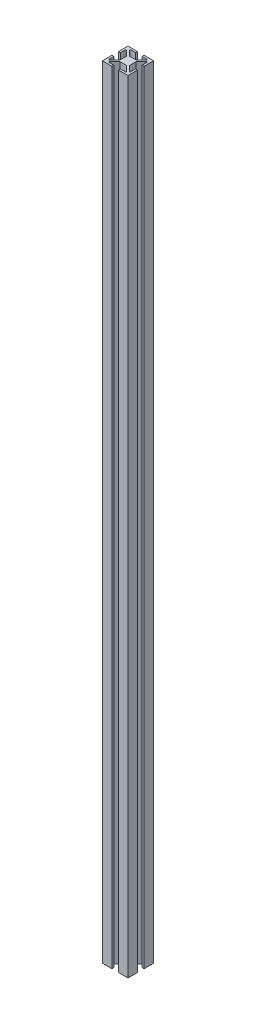
SolidWorks part; units mm, degrees
ref_plane "Plan de face" through (0, 0, 0) normal (0, 0, 1) x (1, 0, 0)
ref_plane "Plan de dessus" through (0, 0, 0) normal (0, 1, 0) x (1, 0, 0)
ref_plane "Plan de droite" through (0, 0, 0) normal (1, 0, 0) x (0, 0, -1)
sketch "Esquisse1" plane through (0, 0, 0) normal (0, 1, 0) x (1, 0, 0)
  line L0 (6.1245, 16.1036) -> (30.6226, 16.1036) construction
  line L6 (-11.5924, 0) -> (12.1076, 0) construction
  line L7 (0, 12.3466) -> (0, -12.7449) construction
  line L12 (-10, -10) -> (10, 10) construction
  line L59 (-10, -2.5) -> (-10, -10)
  line L60 (-10, -2.5) -> (-8.5, -2.5)
  line L69 (-8.5, -2.5) -> (-8.5, -6.2322)
  line L70 (-7.6464, -6.5858) -> (-3.75, -2.6893)
  line L73 (-6.5858, -7.6464) -> (-2.6893, -3.75)
  line L74 (-2.5, -8.5) -> (-6.2322, -8.5)
  line L75 (-2.5, -10) -> (-2.5, -8.5)
  line L76 (-2.5, -10) -> (-10, -10)
  line L77 (-2.5, 10) -> (-2.5, 8.5)
  line L78 (-2.5, 10) -> (-10, 10)
  line L79 (-10, 2.5) -> (-10, 10)
  line L80 (-10, 2.5) -> (-8.5, 2.5)
  line L81 (-8.5, 2.5) -> (-8.5, 6.2322)
  line L82 (-7.6464, 6.5858) -> (-3.75, 2.6893)
  line L83 (-6.5858, 7.6464) -> (-2.6893, 3.75)
  line L84 (-2.5, 8.5) -> (-6.2322, 8.5)
  line L85 (10, 2.5) -> (8.5, 2.5)
  line L86 (10, 2.5) -> (10, 10)
  line L87 (2.5, 10) -> (10, 10)
  line L88 (2.5, 10) -> (2.5, 8.5)
  line L89 (2.5, 8.5) -> (6.2322, 8.5)
  line L90 (6.5858, 7.6464) -> (2.6893, 3.75)
  line L91 (7.6464, 6.5858) -> (3.75, 2.6893)
  line L92 (8.5, 2.5) -> (8.5, 6.2322)
  line L93 (2.5, -10) -> (2.5, -8.5)
  line L94 (2.5, -10) -> (10, -10)
  line L95 (10, -2.5) -> (10, -10)
  line L96 (10, -2.5) -> (8.5, -2.5)
  line L97 (8.5, -2.5) -> (8.5, -6.2322)
  line L98 (7.6464, -6.5858) -> (3.75, -2.6893)
  line L99 (6.5858, -7.6464) -> (2.6893, -3.75)
  line L100 (2.5, -8.5) -> (6.2322, -8.5)
  line L101 (-3.75, 2.6893) -> (-3.75, -2.6893)
  line L102 (-2.6893, -3.75) -> (2.6893, -3.75)
  line L103 (-2.6893, 3.75) -> (2.6893, 3.75)
  line L104 (3.75, 2.6893) -> (3.75, -2.6893)
  arc A0 (-8.5, 6.2322) -> (-7.6464, 6.5858) centre (-8, 6.2322) cw
  arc A1 (-8.5, -6.2322) -> (-7.6464, -6.5858) centre (-8, -6.2322) ccw
  arc A2 (-6.5858, -7.6464) -> (-6.2322, -8.5) centre (-6.2322, -8) ccw
  arc A3 (6.5858, -7.6464) -> (6.2322, -8.5) centre (6.2322, -8) cw
  arc A4 (8.5, -6.2322) -> (7.6464, -6.5858) centre (8, -6.2322) cw
  arc A5 (7.6464, 6.5858) -> (8.5, 6.2322) centre (8, 6.2322) cw
  arc A6 (6.2322, 8.5) -> (6.5858, 7.6464) centre (6.2322, 8) cw
  arc A7 (-6.5858, 7.6464) -> (-6.2322, 8.5) centre (-6.2322, 8) cw
  point P7 (-2.5, -9.25)
  point P8 (2.5, -9.25)
  point P15 (-8.5, -7.4393)
  point P51 (0, 0)
  point P52 (-7.4393, -8.5)
  dimension "D2" = 5
  dimension "D7" = 0.5
  dimension "D1" = 20
  dimension "D3" = 4
  dimension "D4" = 7.5
  dimension "D5" = 1.5
  dimension "D6" = 1.5
extrude "Boss.-Extru.1" add sketch "Esquisse1" along normal blind 610
